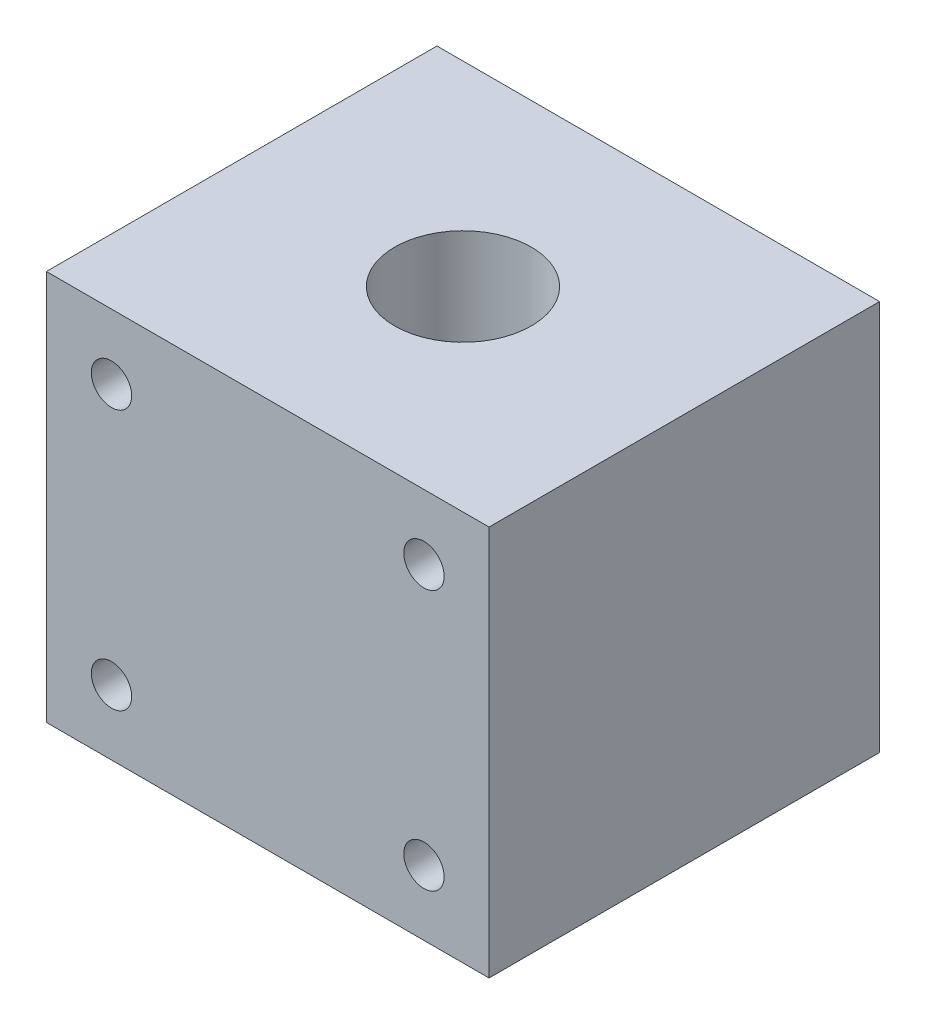
SolidWorks part; units mm, degrees
material "1345 Alloy"
ref_plane "前视基准面" through (0, 0, 0) normal (0, 0, 1) x (1, 0, 0)
ref_plane "上视基准面" through (0, 0, 0) normal (0, 1, 0) x (1, 0, 0)
ref_plane "右视基准面" through (0, 0, 0) normal (1, 0, 0) x (0, 0, -1)
sketch "Sketch1" plane through (0, 0, 0) normal (0, 1, 0) x (1, 0, 0)
  line L0 (0, 0) -> (0, -30)
  line L1 (0, -30) -> (34, -30)
  line L2 (34, -30) -> (34, 0)
  line L3 (34, 0) -> (0, 0)
  line L4 (0, 0) -> (34, -30) construction
  line L5 (34, 0) -> (0, -30) construction
  circle A0 centre (17, -15) radius 5.25
  dimension "D3" = 10.5
  dimension "D1" = 30
  dimension "D2" = 34
extrude "Boss-Extrude1" add sketch "Sketch1" along normal blind 30
sketch "Sketch2" plane through (0, 0, 0) normal (0, -1, 0) x (1, 0, 0)
  line L0 (17, 25.0506) -> (17, 3.8402) construction
  circle A0 centre (17, 15) radius 8 construction
  circle A1 centre (17, 23) radius 1.25
  circle A2 centre (25, 15) radius 1.25
  circle A3 centre (17, 7) radius 1.25
  circle A4 centre (9, 15) radius 1.25
  point P16 (17, 15)
  dimension "D1" = 16
  dimension "D2" = 2.5
  dimension "D3" = 4
extrude "Cut-Extrude1" cut sketch "Sketch2" against normal blind 10 contours A1 | A2 | A3 | A4
cosmetic thread "Cosmetic Thread1" parameters "D2"=3
cosmetic thread "Cosmetic Thread2" parameters "D2"=3
cosmetic thread "Cosmetic Thread3" parameters "D2"=3
cosmetic thread "Cosmetic Thread4" parameters "D2"=3
sketch "Sketch3" plane through (0, 0, 30) normal (0, 0, 1) x (1, 0, 0)
  line L0 (-2.9117, 15) -> (36.8847, 15) construction
  line L1 (0, 30) -> (34, 30) construction
  line L2 (17, 30.5696) -> (17, -0.8942) construction
  line L3 (34, 30) -> (34, 0) construction
  line L4 (5, 30.5696) -> (5, -0.8942) construction
  line L5 (-2.9117, 25) -> (36.8847, 25) construction
  circle A0 centre (5, 25) radius 1.55
  circle A1 centre (29, 25) radius 1.55
  circle A2 centre (29, 5) radius 1.55
  circle A3 centre (5, 5) radius 1.55
  dimension "D5" = 3.1
  dimension "D1" = 15
  dimension "D2" = 17
  dimension "D8" = 24
  dimension "D9" = 20
  dimension "D10" = 24
  dimension "D3" = 12
  dimension "D4" = 10
  dimension "D6" = 2
  dimension "D7" = 2
extrude "Cut-Extrude2" cut sketch "Sketch3" against normal blind 10
cosmetic thread "Cosmetic Thread9" parameters "D2"=4
cosmetic thread "Cosmetic Thread10" parameters "D2"=4
cosmetic thread "Cosmetic Thread11" parameters "D2"=4
cosmetic thread "Cosmetic Thread12" parameters "D2"=4
